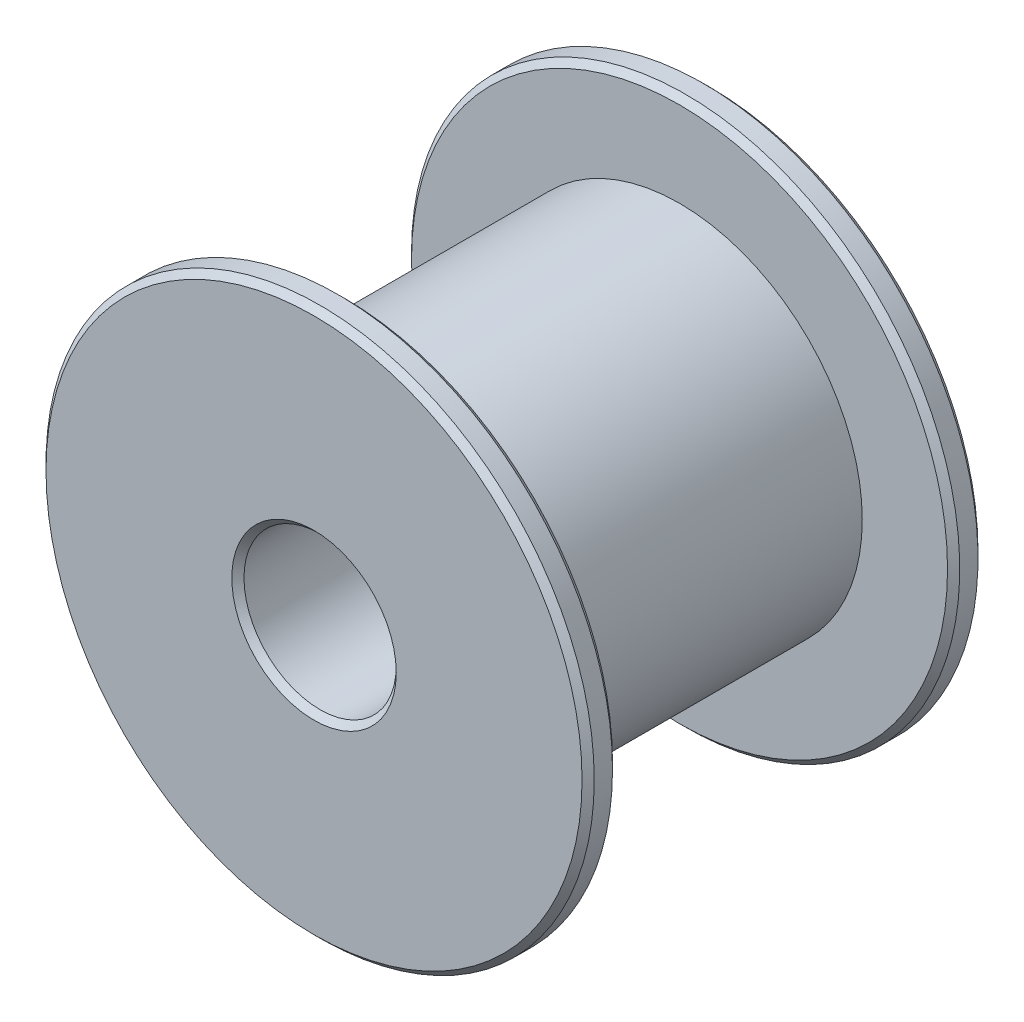
SolidWorks part; units mm, degrees
ref_plane "Front" through (0, 0, 0) normal (0, 0, 1) x (1, 0, 0)
ref_plane "Top" through (0, 0, 0) normal (0, 1, 0) x (1, 0, 0)
ref_plane "Right" through (0, 0, 0) normal (1, 0, 0) x (0, 0, -1)
sketch "Skizze1" plane through (0, 0, 0) normal (0, 0, 1) x (1, 0, 0)
  circle A0 centre (0, 0) radius 6
  dimension "D1" = 12
extrude "Aufsatz-Linear austragen1" add sketch "Skizze1" along normal mid plane 11
sketch "Skizze2" plane through (0, 0, 5.5) normal (0, 0, 1) x (1, 0, 0)
  circle A0 centre (0, 0) radius 9
  dimension "D1" = 18
extrude "Aufsatz-Linear austragen2" add sketch "Skizze2" along normal blind 1
mirror "Spiegeln1" about plane through (0, 0, 0) normal (0, 0, 1) of "Aufsatz-Linear austragen2"
sketch "Skizze3" plane through (0, 0, -6.5) normal (0, 0, -1) x (-1, 0, 0)
  circle A0 centre (0, 0) radius 2.5
  dimension "D1" = 5
extrude "Schnitt-Linear austragen1" cut sketch "Skizze3" against normal through all
chamfer "Fase1" distance 0.2 angle 45 6 edges at (-2.5, 0, -6.5) (-2.5, 0, 6.5) (9, 0, 6.5) (9, 0, 5.5) (9, 0, -5.5) (9, 0, -6.5)
sketch "Skizze4" plane through (0, 0, 6.5) normal (0, 0, 1) x (1, 0, 0)
  circle A0 centre (0, 0) radius 9.6375
extrude "Schnitt-Linear austragen2" [suppressed] cut sketch "Skizze4" against normal up to surface (1 mm away)
